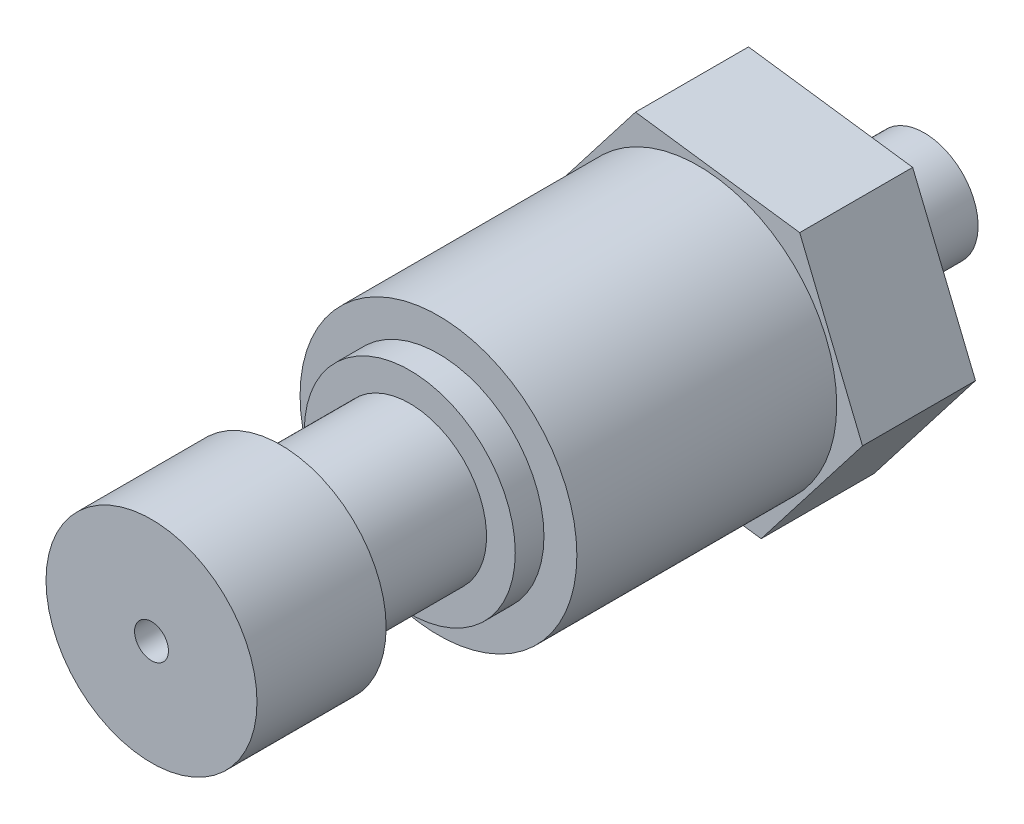
SolidWorks part; units mm, degrees
ref_plane "Front Plane" through (0, 0, 0) normal (0, 0, 1) x (1, 0, 0)
ref_plane "Top Plane" through (0, 0, 0) normal (0, 1, 0) x (1, 0, 0)
ref_plane "Right Plane" through (0, 0, 0) normal (1, 0, 0) x (0, 0, -1)
sketch "Sketch1" plane through (0, 0, 0) normal (0, 0, 1) x (1, 0, 0)
  line L1 (14.5318, -1.9697) -> (8.9717, 11.6001)
  line L2 (8.9717, 11.6001) -> (-5.5601, 13.5698)
  line L3 (-5.5601, 13.5698) -> (-14.5318, 1.9697)
  line L4 (-14.5318, 1.9697) -> (-8.9717, -11.6001)
  line L5 (-8.9717, -11.6001) -> (5.5601, -13.5698)
  line L6 (5.5601, -13.5698) -> (14.5318, -1.9697)
  circle A0 centre (0, 0) radius 12.7 construction
  dimension "D1" = 25.4
extrude "Boss-Extrude1" add sketch "Sketch1" along normal blind 10
sketch "Sketch2" plane through (0, 0, 10) normal (0, 0, 1) x (1, 0, 0)
  circle A0 centre (0, 0) radius 12.25
  dimension "D1" = 24.5
extrude "Boss-Extrude2" add sketch "Sketch2" along normal blind 23
sketch "Sketch5" plane through (0, 0, 0) normal (0, 0, -1) x (-1, 0, 0)
  circle A0 centre (0, 0) radius 4.7625
  dimension "D1" = 9.525
extrude "Boss-Extrude3" add sketch "Sketch5" along normal blind 10
sketch "Sketch6" plane through (0, 0, 33) normal (0, 0, 1) x (1, 0, 0)
  circle A0 centre (0, 0) radius 9.3375
extrude "Boss-Extrude4" add sketch "Sketch6" along normal blind 2.54
sketch "Sketch7" plane through (0, 0, 35.54) normal (0, 0, 1) x (1, 0, 0)
  circle A0 centre (0, 0) radius 6.7937
extrude "Boss-Extrude5" add sketch "Sketch7" along normal blind 11.43
sketch "Sketch8" plane through (0, 0, 46.97) normal (0, 0, 1) x (1, 0, 0)
  circle A0 centre (0, 0) radius 9.3375
extrude "Boss-Extrude6" add sketch "Sketch8" along normal blind 11.43
sketch "Sketch9" plane through (0, 0, 58.4) normal (0, 0, 1) x (1, 0, 0)
  circle A0 centre (0, 0) radius 1.5
  dimension "D1" = 3
extrude "Cut-Extrude1" cut sketch "Sketch9" against normal through all
